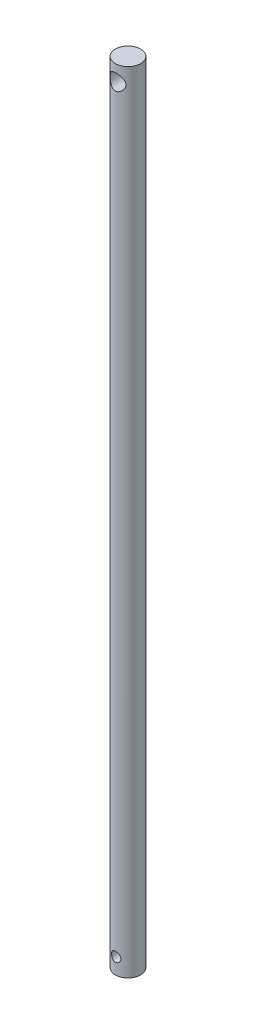
SolidWorks part; units mm, degrees
ref_plane "Front Plane" through (0, 0, 0) normal (0, 0, 1) x (1, 0, 0)
ref_plane "Top Plane" through (0, 0, 0) normal (0, 1, 0) x (1, 0, 0)
ref_plane "Right Plane" through (0, 0, 0) normal (1, 0, 0) x (0, 0, -1)
sketch "Sketch1" plane through (0, 0, 0) normal (0, 1, 0) x (1, 0, 0)
  circle A0 centre (0, 0) radius 4
  dimension "D1" = 8
extrude "Boss-Extrude1" add sketch "Sketch1" along normal blind 250
sketch "Sketch2" plane through (0, 0, 0) normal (0, 0, 1) x (1, 0, 0)
  line L0 (-4, 125) -> (4, 125) construction
  line L1 (-4, 250) -> (-4, 0) construction
  line L2 (4, 0) -> (4, 250) construction
  line L3 (4, 250) -> (-4, 250) construction
  circle A0 centre (0, 5) radius 1.5
  circle A2 centre (0, 245) radius 2.5
  point P13 (0, 0)
  dimension "D1" = 3
  dimension "D3" = 5
  dimension "D2" = 5
  dimension "D4" = 5
extrude "Cut-Extrude1" cut sketch "Sketch2" against normal through all both and the other way through all
equation "\"Rod Diameter\"= 8mm"
equation "\"Rod Length\"= 250mm"
equation "\"D1@Sketch1\"=\"Rod Diameter\""
equation "\"D1@Boss-Extrude1\"=\"Rod Length\""
